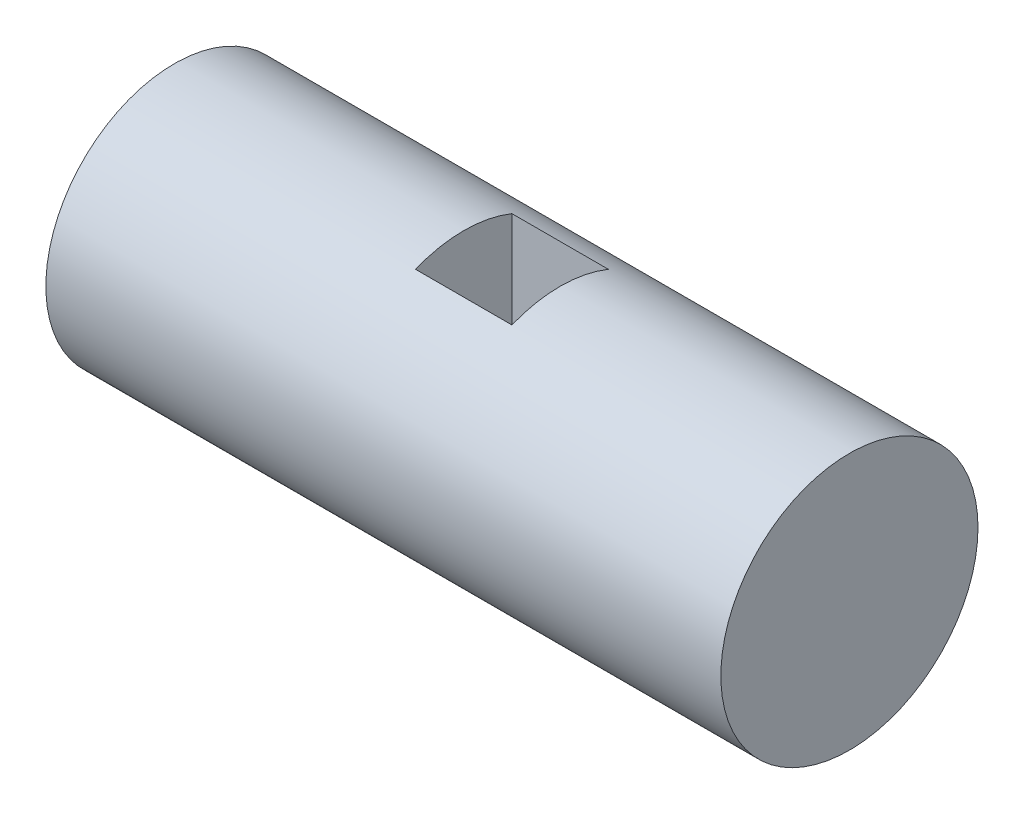
SolidWorks part; units mm, degrees
material "Cast Carbon Steel"
ref_plane "Front Plane" through (0, 0, 0) normal (0, 0, 1) x (1, 0, 0)
ref_plane "Top Plane" through (0, 0, 0) normal (0, 1, 0) x (1, 0, 0)
ref_plane "Right Plane" through (0, 0, 0) normal (1, 0, 0) x (0, 0, -1)
sketch "Sketch1" plane through (0, 0, 0) normal (1, 0, 0) x (0, 0, -1)
  circle A0 centre (0, 0) radius 20
  dimension "D1" = 40
extrude "Boss-Extrude1" add sketch "Sketch1" along normal blind 105
sketch "Sketch2" plane through (0, 0, 0) normal (0, 1, 0) x (1, 0, 0)
  line L0 (105, -20) -> (105, 20) construction
  line L1 (45, 7.5) -> (60, 7.5)
  line L2 (45, 7.5) -> (45, -7.5)
  line L3 (45, -7.5) -> (60, -7.5)
  line L4 (60, 7.5) -> (60, -7.5)
  line L5 (45, 7.5) -> (60, -7.5) construction
  line L6 (45, -7.5) -> (60, 7.5) construction
  line L8 (0, 0) -> (105, 0) construction
  point P0 (52.5, 0)
  dimension "D1" = 15
extrude "Cut-Extrude1" cut sketch "Sketch2" against normal up to next and the other way up to next
